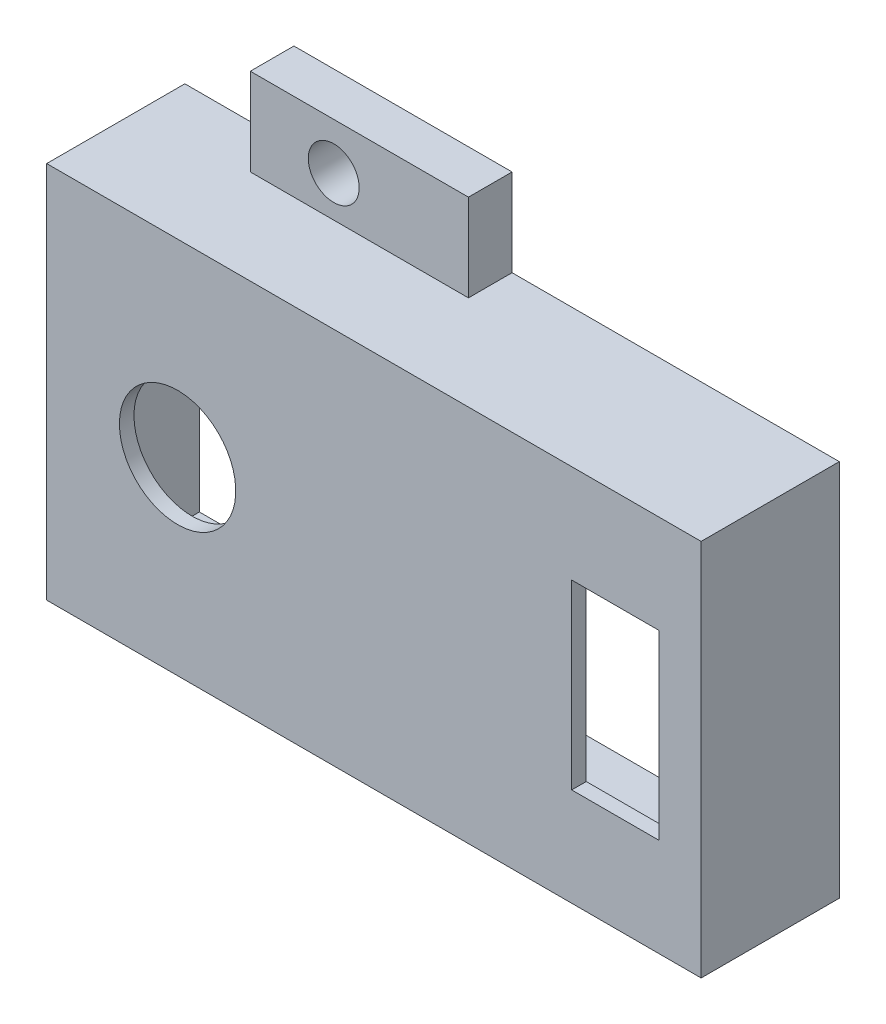
SolidWorks part; units mm, degrees
ref_plane "Front Plane" through (0, 0, 0) normal (0, 0, 1) x (1, 0, 0)
ref_plane "Top Plane" through (0, 0, 0) normal (0, 1, 0) x (1, 0, 0)
ref_plane "Right Plane" through (0, 0, 0) normal (1, 0, 0) x (0, 0, -1)
sketch "Sketch1" plane through (0, 0, 0) normal (0, 0, 1) x (1, 0, 0)
  line L1 (-22.5, -13) -> (22.5, -13)
  line L2 (-22.5, -13) -> (-22.5, 13)
  line L3 (-22.5, 13) -> (22.5, 13)
  line L4 (22.5, -13) -> (22.5, 13)
  line L5 (-22.5, -13) -> (22.5, 13) construction
  line L6 (-22.5, 13) -> (22.5, -13) construction
  point P0 (0, 0)
  dimension "D1" = 26
  dimension "D2" = 45
extrude "Boss-Extrude2" add sketch "Sketch1" along normal blind 9.5
shell "Shell2" thickness 1
sketch "Sketch2" plane through (0, 0, 8.5) normal (0, 0, -1) x (-1, 0, 0)
  line L0 (-21.5, 10.6922) -> (21.5, 10.6922) construction
  line L1 (-21.5, -12) -> (-21.5, 12) construction
  line L2 (21.5, 12) -> (21.5, -12) construction
  line L4 (-13.6, -6.25) -> (-19.6, -6.25)
  line L5 (-13.6, -6.25) -> (-13.6, 6.25)
  line L6 (-13.6, 6.25) -> (-19.6, 6.25)
  line L7 (-19.6, -6.25) -> (-19.6, 6.25)
  line L8 (-13.6, -6.25) -> (-19.6, 6.25) construction
  line L9 (-13.6, 6.25) -> (-19.6, -6.25) construction
  circle A0 centre (13.5, 0) radius 4
  point P8 (-16.6, 0)
  point P13 (-15.05, 0)
  point P14 (-14.6, 0)
  dimension "D1" = 8
  dimension "D2" = 8
  dimension "D3" = 12.5
  dimension "D4" = 6
  dimension "D5" = 33.1
extrude "Cut-Extrude1" cut sketch "Sketch2" against normal blind 9.5
sketch "Sketch3" plane through (0, 0, 0) normal (0, 0, -1) x (-1, 0, 0)
  line L0 (-22.5, 13) -> (22.5, 13) construction
  line L1 (0, 13) -> (15, 13)
  line L2 (0, 13) -> (0, 19)
  line L3 (0, 19) -> (15, 19)
  line L4 (15, 13) -> (15, 19)
  line L5 (22.5, -13) -> (-22.5, -13) construction
  line L6 (0, -13) -> (15, -13)
  line L7 (0, -13) -> (0, -19)
  line L8 (0, -19) -> (15, -19)
  line L9 (15, -13) -> (15, -19)
  dimension "D1" = 15
  dimension "D2" = 6
  dimension "D3" = 6
extrude "Boss-Extrude4" add sketch "Sketch3" against normal blind 3
sketch "Sketch4" plane through (0, 0, 3) normal (0, 0, 1) x (1, 0, 0)
  circle A0 centre (-8.6743, -16.2126) radius 1.6
  dimension "D1" = 3.2
extrude "Cut-Extrude2" cut sketch "Sketch4" against normal blind 9
sketch "Sketch5" plane through (0, 0, 3) normal (0, 0, 1) x (1, 0, 0)
  circle A0 centre (-9.2627, 15.7982) radius 1.75
  point P2 (-9.2627, 15.7982)
  dimension "D1" = 3.5
extrude "Cut-Extrude3" cut sketch "Sketch5" against normal blind 9
